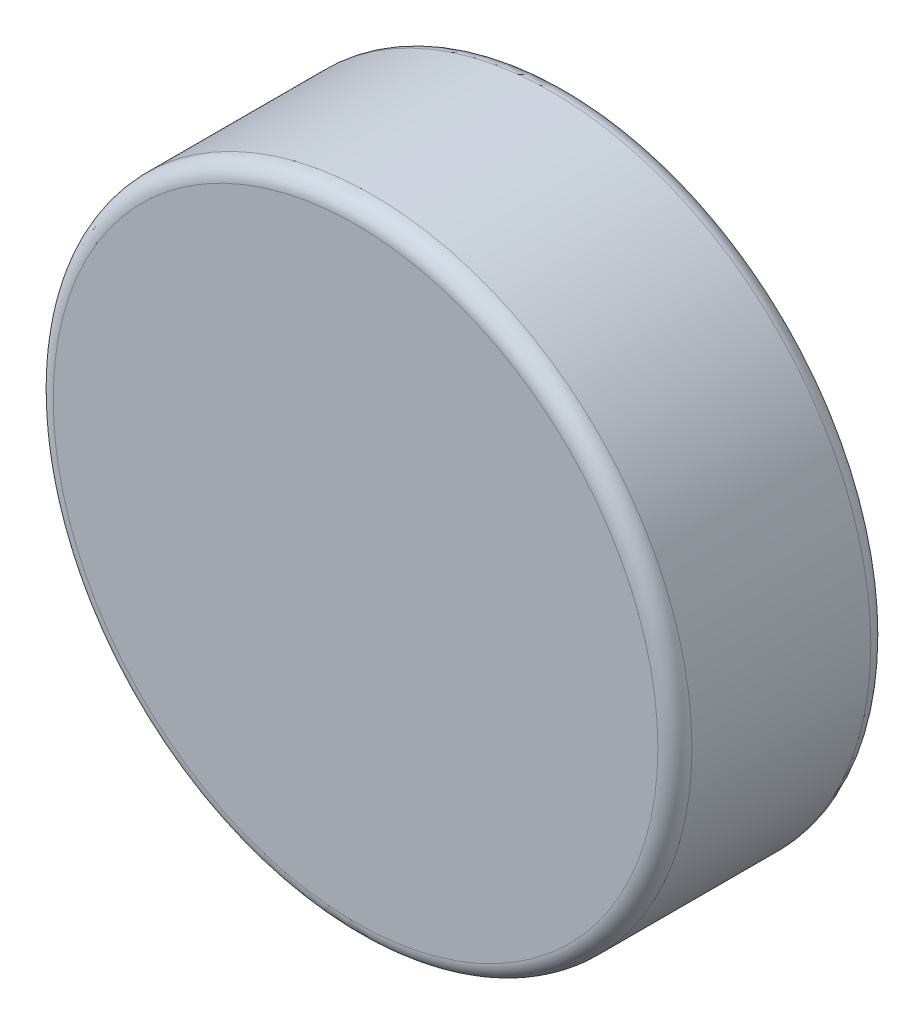
SolidWorks part; units mm, degrees
ref_plane "Front Plane" through (0, 0, 0) normal (0, 0, 1) x (1, 0, 0)
ref_plane "Top Plane" through (0, 0, 0) normal (0, 1, 0) x (1, 0, 0)
ref_plane "Right Plane" through (0, 0, 0) normal (1, 0, 0) x (0, 0, -1)
sketch "Sketch1" plane through (0, 0, 0) normal (0, 0, 1) x (1, 0, 0)
  circle A0 centre (0, 0) radius 2.3813 construction
  dimension "OD" = 4.7625
sketch "Sketch2" plane through (0, 0, 0) normal (1, 0, 0) x (0, 0, -1)
  line L0 (-0.7937, 0) -> (0.7938, 0) construction
  line L1 (0, 2.3813) -> (0, -2.3813) construction
  line L3 (-0.7938, 2.3813) -> (0.7937, 2.3813)
  line L4 (-0.7938, 2.3813) -> (-0.7938, -2.3813)
  line L5 (-0.7938, -2.3813) -> (0.7937, -2.3813)
  line L6 (0.7937, 2.3813) -> (0.7937, -2.3813)
  point P4 (0, 0)
  point P12 (0, 2.3813)
  dimension "Thickness" = 1.5875
sketch "Sketch3" plane through (0, 0, 0) normal (0, 0, 1) x (1, 0, 0)
  circle A0 centre (0, 0) radius 2.3813 construction
  circle A1 centre (0, 0) radius 2.3813
extrude "Boss-Extrude1" add sketch "Sketch3" along normal up to vertex (0.7937 mm away) and the other way up to vertex (0.7937 mm away) up to point (0, 2.3813, 0.7938) other way up to point (0, 2.3813, -0.7937)
fillet "Fillet1" radius 0.127 2 edges at (2.3813, 0, -0.7937) (2.3813, 0, 0.7938)
equation "\"Fillet@Fillet1\"=.005"
